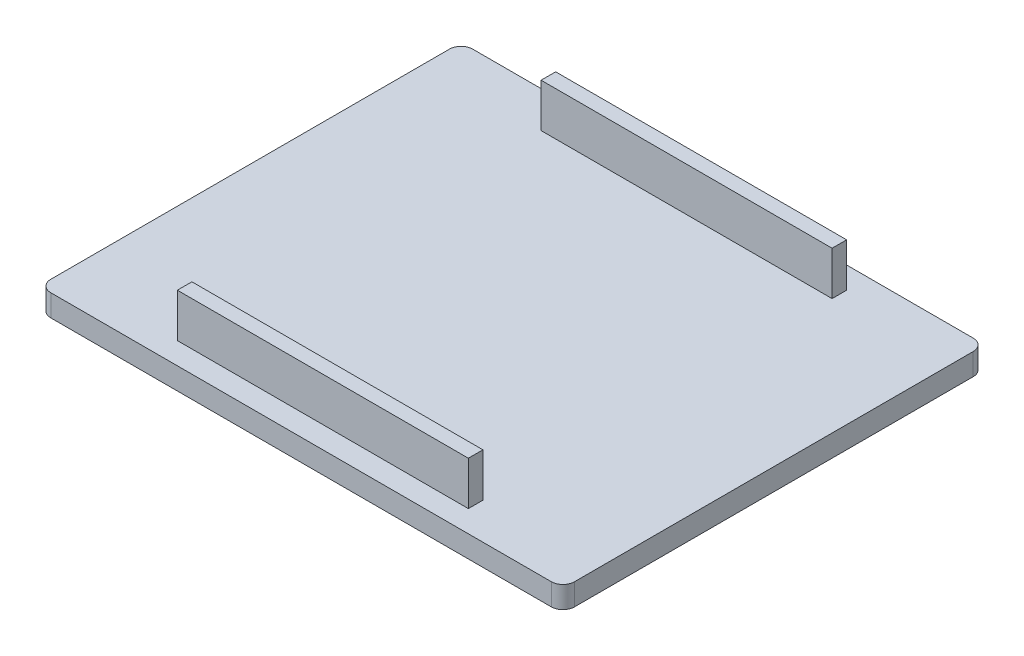
SolidWorks part; units mm, degrees
ref_plane "Front Plane" through (0, 0, 0) normal (0, 0, 1) x (1, 0, 0)
ref_plane "Top Plane" through (0, 0, 0) normal (0, 1, 0) x (1, 0, 0)
ref_plane "Right Plane" through (0, 0, 0) normal (1, 0, 0) x (0, 0, -1)
sketch "Sketch1" plane through (0, 0, 0) normal (0, 1, 0) x (1, 0, 0)
  line L1 (0, 0) -> (36, 0)
  line L2 (0, 0) -> (0, -29)
  line L3 (0, -29) -> (36, -29)
  line L4 (36, 0) -> (36, -29)
  dimension "D1" = 29
  dimension "D2" = 36
extrude "Boss-Extrude1" add sketch "Sketch1" along normal blind 1.5
fillet "Fillet1" radius 0.8 4 edges at (0, 0.75, 29) (0, 0.75, 0) (36, 0.75, 0) (36, 0.75, 29)
sketch "Sketch2" plane through (0, 1.5, 0) normal (0, 1, 0) x (1, 0, 0)
  line L0 (35.2, 0) -> (0.8, 0) construction
  line L1 (8, -1.5) -> (28, -1.5)
  line L2 (8, -1.5) -> (8, -2.5)
  line L3 (8, -2.5) -> (28, -2.5)
  line L4 (28, -1.5) -> (28, -2.5)
  line L5 (8, -27.5) -> (28, -27.5)
  line L6 (8, -27.5) -> (8, -26.5)
  line L7 (8, -26.5) -> (28, -26.5)
  line L8 (28, -27.5) -> (28, -26.5)
  line L9 (0.8, -29) -> (35.2, -29) construction
  line L10 (36, -28.2) -> (36, -0.8) construction
  dimension "D1" = 20
  dimension "D2" = 20
  dimension "D3" = 1
  dimension "D4" = 1
  dimension "D5" = 1.5
  dimension "D6" = 1.5
  dimension "D7" = 8
  dimension "D8" = 8
extrude "Boss-Extrude2" add sketch "Sketch2" along normal blind 3
